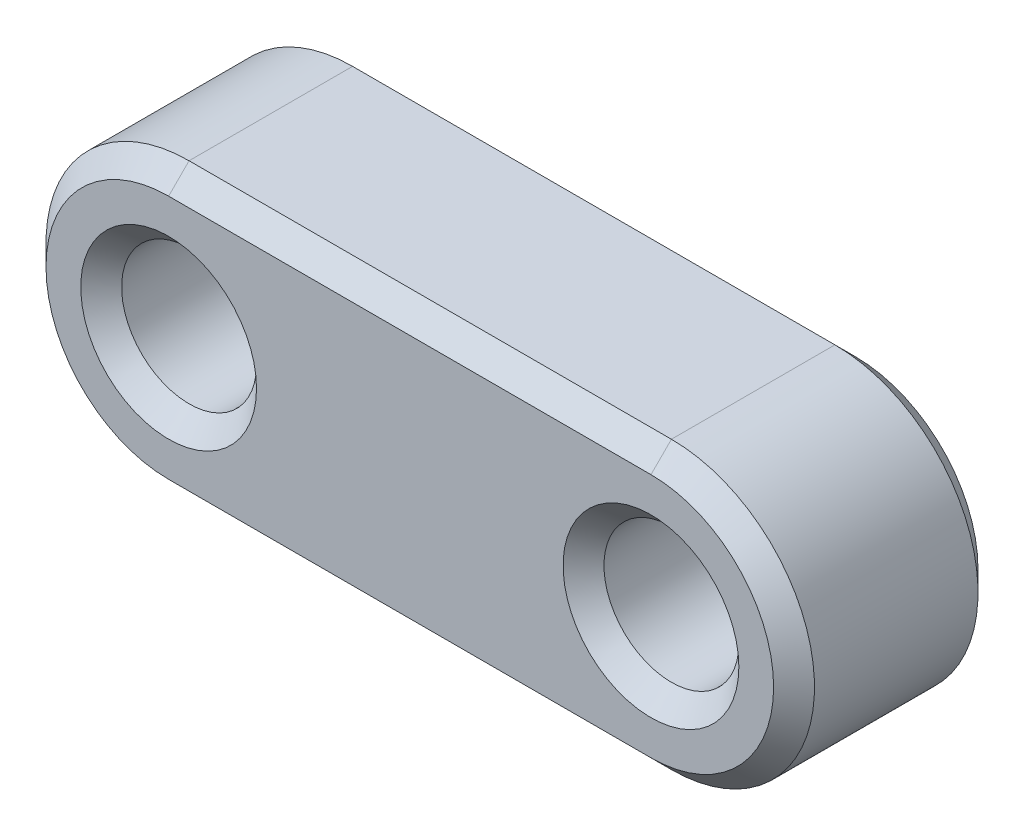
SolidWorks part; units mm, degrees
ref_plane "前视基准面" through (0, 0, 0) normal (0, 0, 1) x (1, 0, 0)
ref_plane "上视基准面" through (0, 0, 0) normal (0, 1, 0) x (1, 0, 0)
ref_plane "右视基准面" through (0, 0, 0) normal (1, 0, 0) x (0, 0, -1)
sketch "草图1" plane through (0, 0, 0) normal (0, 0, 1) x (1, 0, 0)
  line L0 (-5.9, 0) -> (5.9, 0) construction
  line L1 (-5.9, 3.5) -> (5.9, 3.5)
  line L2 (-5.9, -3.5) -> (5.9, -3.5)
  arc A0 (-5.9, 3.5) -> (-5.9, -3.5) centre (-5.9, 0) ccw
  arc A1 (5.9, -3.5) -> (5.9, 3.5) centre (5.9, 0) ccw
  circle A2 centre (5.9, 0) radius 1.65
  circle A3 centre (-5.9, 0) radius 1.65
  point P2 (0, 0)
  dimension "D2" = 3.5
  dimension "D3" = 3.3
  dimension "D1" = 11.8
extrude "凸台-拉伸1" add sketch "草图1" along normal blind 5
chamfer "倒角1" distance 0.5 angle 45 12 edges at (7.55, 0, 0) (-4.25, 0, 0) (9.4, 0, 0) (0, 3.5, 0) (0, -3.5, 0) (-9.4, 0, 0) (0, -3.5, 5) (9.4, 0, 5) (-9.4, 0, 5) (0, 3.5, 5) (7.55, 0, 5) (-4.25, 0, 5)
